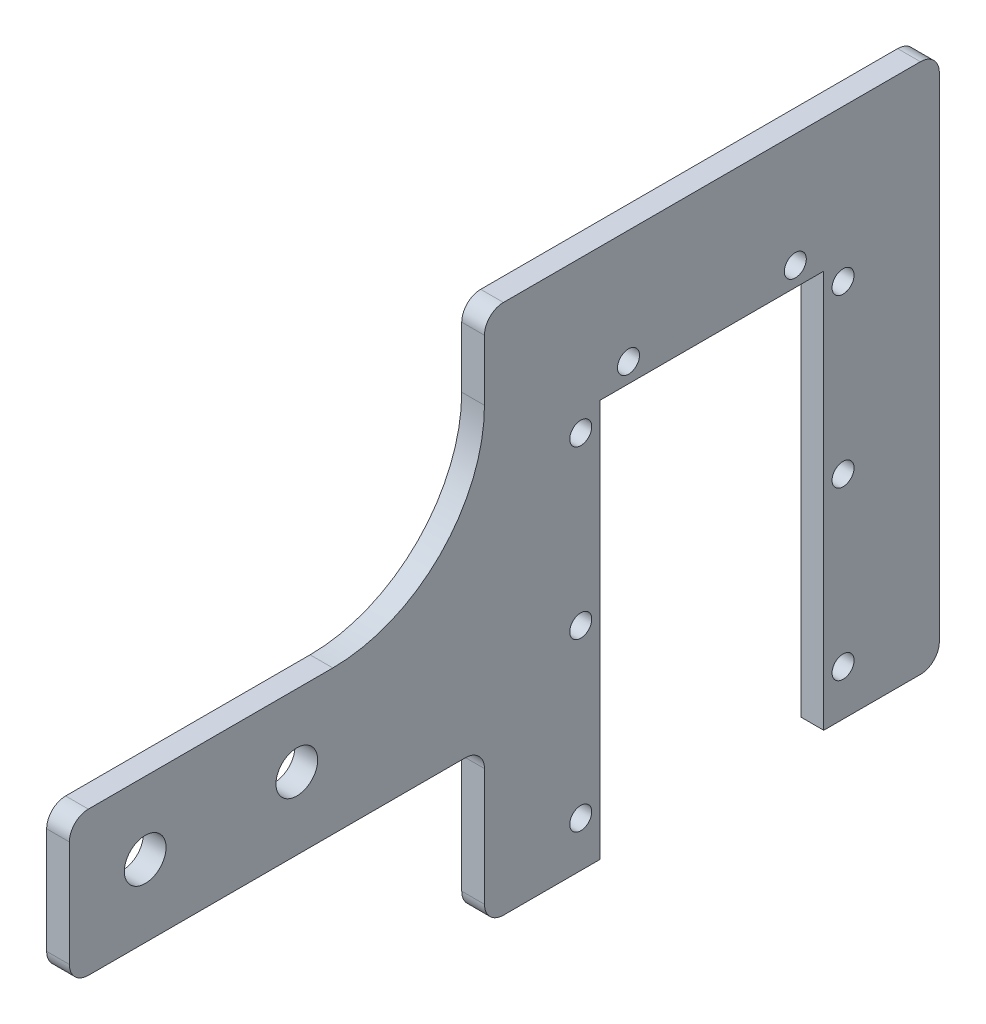
SolidWorks part; units mm, degrees
ref_plane "Front Plane" through (0, 0, 0) normal (0, 0, 1) x (1, 0, 0)
ref_plane "Top Plane" through (0, 0, 0) normal (0, 1, 0) x (1, 0, 0)
ref_plane "Right Plane" through (0, 0, 0) normal (1, 0, 0) x (0, 0, -1)
sketch "Mounting points" plane through (0, 0, 0) normal (1, 0, 0) x (0, 0, -1)
  line L0 (-17.3, 0) -> (17.3, 0) construction
  line L1 (-17.3, 18) -> (-17.3, 40) construction
  line L2 (17.3, 18) -> (17.3, 40) construction
  line L3 (-17.3, 18) -> (-17.3, -4) construction
  line L4 (17.3, 18) -> (17.3, -4) construction
  line L5 (11, 45) -> (-11, 45) construction
  line L6 (14.5, 42.2) -> (-14.5, 42.2) construction
  line L7 (14.5, 42.2) -> (14.5, -14.5) construction
  line L8 (14.5, -14.5) -> (-14.5, -14.5) construction
  line L9 (-14.5, 42.2) -> (-14.5, -14.5) construction
  line L10 (0, 50.8505) -> (0, -49949.1495) construction
  point P5 (0, 0)
  point P18 (0, 45)
  dimension "D1" = 34.6
  dimension "D2" = 22
  dimension "D3" = 4
  dimension "D4" = 29
  dimension "D5" = 14.5
  dimension "D6" = 42.2
  dimension "D7" = 22
  dimension "D8" = 45
sketch "Sketch8" plane through (0, 0, 0) normal (1, 0, 0) x (0, 0, -1)
  line L0 (30, 60) -> (-30, 60)
  line L9 (-17.3, 0) -> (17.3, 0) construction
  line L10 (30, 60) -> (30, -10)
  line L11 (14.75, -10) -> (30, -10)
  line L12 (-14.75, 42.45) -> (-14.75, -14.5)
  line L13 (14.75, 42.45) -> (-14.75, 42.45)
  line L14 (14.75, -14.5) -> (14.75, 42.45)
  line L15 (-14.75, 42.45) -> (-14.75, -10)
  line L16 (0, 200050.8505) -> (0, -249949.1495) construction
  line L17 (-30, 60) -> (-30, -10)
  line L18 (-30, -10) -> (-14.75, -10)
  line L24 (14.75, 42.45) -> (-14.75, 42.45)
  line L25 (14.75, -10) -> (14.75, 42.45)
  dimension "D2" = 60
  dimension "D3" = 10
  dimension "D4" = 30
  dimension "D5" = 30
  dimension "D1" = 0.25
extrude "Boss-Extrude2" add sketch "Sketch8" along normal mid plane 3 separate body
sketch "Sketch11" plane through (0, 0, 0) normal (1, 0, 0) x (0, 0, -1)
  line L0 (-14.75, -10) -> (-14.75, 42.45) construction
  line L1 (-84.75, 10.5) -> (-84.75, 29.5)
  line L2 (-84.75, 10.5) -> (-14.75, 10.5)
  line L3 (-14.75, 10.5) -> (-14.75, 29.5)
  line L4 (-84.75, 29.5) -> (-14.75, 29.5)
  line L6 (-545.3956, 29.5) -> (-45.3956, 29.5) construction
  dimension "D1" = 70
  dimension "D2" = 19
extrude "Boss-Extrude3" add sketch "Sketch11" along normal mid plane 3
hole_wizard "M5 Clearance Hole1" positions "Sketch10" profile "Sketch9" hole size "M5" standard "ANSI Metric" end condition up to next
sketch "Sketch10" plane through (1.5, 0, 0) normal (1, 0, 0) x (0, 0, -1)
  line L0 (-84.75, 29.5) -> (-84.75, 10.5) construction
  point P0 (-74.75, 20)
  point P5 (-54.75, 20)
  dimension "D1" = 20
  dimension "D2" = 10
sketch "Sketch9" plane through (1.5, 20, 74.75) normal (0, 1, 0) x (0, 0, -1)
  line L0 (0, 0) -> (0, 3)
  line L1 (0, 3) -> (2.75, 3)
  line L2 (2.75, 3) -> (2.75, 0)
  line L5 (2.75, 0) -> (0, 0)
  line L11 (0, -6.35) -> (0, 107.95) construction
  dimension "Thru Hole Dia." = 5.5
  dimension "Thru Hole Depth" = 3
fillet "Fillet1" radius 2.5 2 edges at (0, 10.5, 84.75) (0, 29.5, 84.75)
fillet "Fillet2" radius 2.5 5 edges at (0, -10, -30) (0, -10, 30) (0, 60, -30) (0, 60, 30) (0, 10.5, 30)
hole_wizard "M2.5 Clearance Hole1" positions "Sketch14" profile "Sketch13" hole size "M2.5" standard "ANSI Metric" end condition up to next
sketch "Sketch14" plane through (1.5, 0, 0) normal (1, 0, 0) x (0, 0, -1)
  point P0 (17.3, 40)
  point P4 (79.7283, 74.7436)
  point P6 (17.3, 18)
  point P9 (17.3, -4)
  point P12 (-17.3, -4)
  point P15 (-17.3, 18)
  point P18 (-17.3, 40)
  point P21 (-11, 45)
  point P24 (11, 45)
sketch "Sketch13" plane through (1.5, 40, -17.3) normal (0, 1, 0) x (0, 0, -1)
  line L0 (0, 0) -> (0, 3)
  line L1 (0, 3) -> (1.45, 3)
  line L2 (1.45, 3) -> (1.45, 0)
  line L5 (1.45, 0) -> (0, 0)
  line L11 (0, -6.35) -> (0, 107.95) construction
  dimension "Thru Hole Dia." = 2.9
  dimension "Thru Hole Depth" = 3
fillet "Fillet3" radius 20 1 edges at (0, 29.5, 30)
